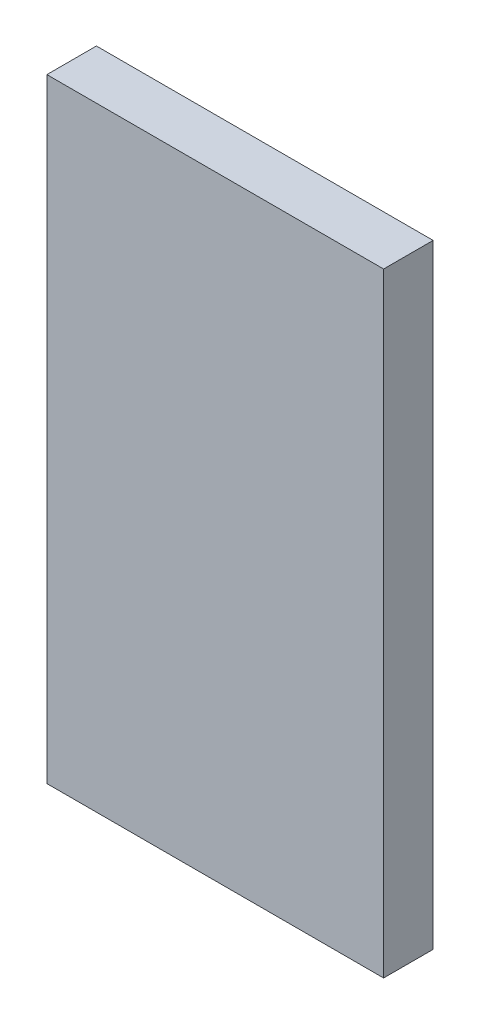
SolidWorks part; units mm, degrees
ref_plane "Plan de face" through (0, 0, 0) normal (0, 0, 1) x (1, 0, 0)
ref_plane "Plan de dessus" through (0, 0, 0) normal (0, 1, 0) x (1, 0, 0)
ref_plane "Plan de droite" through (0, 0, 0) normal (1, 0, 0) x (0, 0, -1)
sketch "Esquisse1" plane through (0, 0, 0) normal (0, 0, 1) x (1, 0, 0)
  line L1 (-14.0278, 8.8487) -> (19.9722, 8.8487)
  line L2 (-14.0278, 8.8487) -> (-14.0278, -53.1513)
  line L3 (-14.0278, -53.1513) -> (19.9722, -53.1513)
  line L4 (19.9722, 8.8487) -> (19.9722, -53.1513)
  dimension "D1" = 34
  dimension "D2" = 62
extrude "Boss.-Extru.1" add sketch "Esquisse1" along normal blind 5
